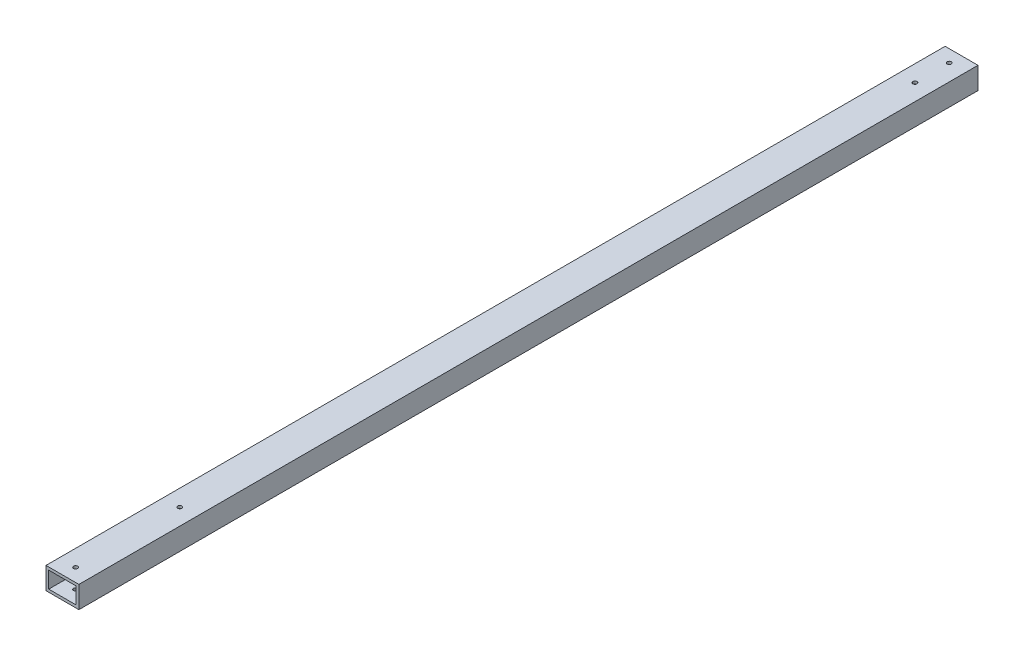
SolidWorks part; units mm, degrees
ref_plane "Front Plane" through (0, 0, 0) normal (0, 0, 1) x (1, 0, 0)
ref_plane "Top Plane" through (0, 0, 0) normal (0, 1, 0) x (1, 0, 0)
ref_plane "Right Plane" through (0, 0, 0) normal (1, 0, 0) x (0, 0, -1)
sketch "Sketch1" plane through (0, 0, 0) normal (0, 0, 1) x (1, 0, 0)
  line L1 (-15.875, -9.525) -> (15.875, -9.525)
  line L2 (-15.875, -9.525) -> (-15.875, 9.525)
  line L3 (-15.875, 9.525) -> (15.875, 9.525)
  line L4 (15.875, -9.525) -> (15.875, 9.525)
  line L5 (-15.875, -9.525) -> (15.875, 9.525) construction
  line L6 (-15.875, 9.525) -> (15.875, -9.525) construction
  line L7 (-19.05, -12.7) -> (19.05, -12.7)
  line L8 (-19.05, -12.7) -> (-19.05, 12.7)
  line L9 (-19.05, 12.7) -> (19.05, 12.7)
  line L10 (19.05, -12.7) -> (19.05, 12.7)
  line L11 (-19.05, -12.7) -> (19.05, 12.7) construction
  line L12 (-19.05, 12.7) -> (19.05, -12.7) construction
  point P0 (0, 0)
  point P6 (0, 0)
extrude "Boss-Extrude1" add sketch "Sketch1" along normal blind 520.7 and the other way blind 520.7
sketch "Sketch2" plane through (0, 12.7, 0) normal (0, 1, 0) x (1, 0, 0)
  line L0 (19.05, -520.7) -> (-19.05, -520.7)
  line L1 (-19.05, -520.7) -> (0, -520.7)
  line L2 (0, -520.7) -> (0, -505.46)
  line L3 (0, -505.46) -> (0, -384.81) construction
  circle A0 centre (0, -384.81) radius 2.3813
  circle A1 centre (0, -505.46) radius 2.3813
extrude "Cut-Extrude1" cut sketch "Sketch2" against normal blind 520.7
sketch "Sketch3" plane through (0, 12.7, 0) normal (0, 1, 0) x (1, 0, 0)
  line L0 (-19.05, 520.7) -> (19.05, 520.7)
  line L1 (19.05, 520.7) -> (0, 520.7)
  line L2 (0, 520.7) -> (0, 506.4125)
  line L3 (0, 506.4125) -> (10, 506.4125)
  line L4 (10, 506.4125) -> (10, 466.725)
  line L5 (10, 466.725) -> (0, 466.725)
  circle A0 centre (0, 506.4125) radius 2.3813
  circle A1 centre (0, 466.725) radius 2.3813
extrude "Cut-Extrude2" cut sketch "Sketch3" against normal blind 100
